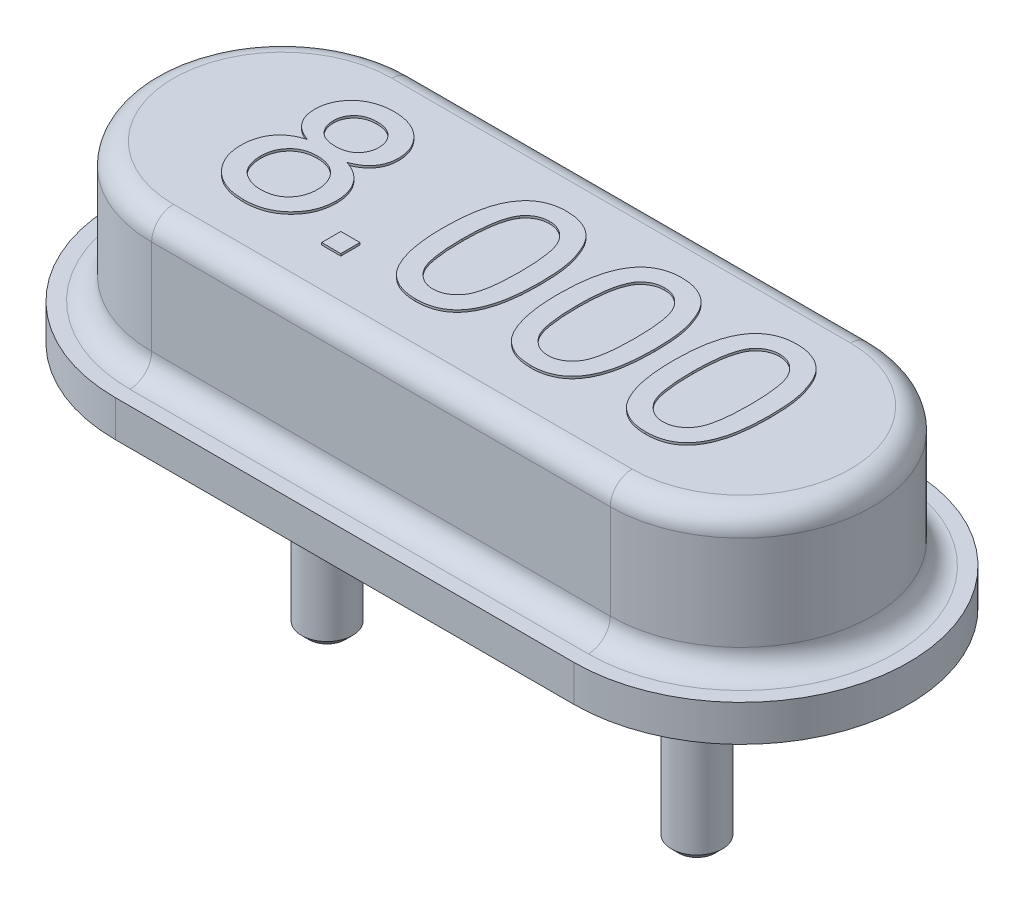
SolidWorks part; units mm, degrees
ref_plane "Front" through (0, 0, 0) normal (0, 0, 1) x (1, 0, 0)
ref_plane "Top" through (0, 0, 0) normal (0, 1, 0) x (1, 0, 0)
ref_plane "Right" through (0, 0, 0) normal (1, 0, 0) x (0, 0, -1)
sketch "Sketch1" plane through (0, 0, 0) normal (0, 1, 0) x (1, 0, 0)
  line L0 (-3.15, 0) -> (3.15, 0) construction
  line L1 (-3.15, 2.3) -> (3.15, 2.3)
  line L2 (-3.15, -2.3) -> (3.15, -2.3)
  arc A0 (-3.15, 2.3) -> (-3.15, -2.3) centre (-3.15, 0) ccw
  arc A1 (3.15, -2.3) -> (3.15, 2.3) centre (3.15, 0) ccw
  point P3 (0, 0)
  dimension "D2" = 10.9
  dimension "D1" = 4.6
extrude "Boss-Extrude1" add sketch "Sketch1" along normal blind 0.5
sketch "Sketch2" plane through (0, 0.5, 0) normal (0, 1, 0) x (1, 0, 0)
  line L4 (-3.15, -1.8) -> (3.15, -1.8)
  line L5 (3.15, 1.8) -> (-3.15, 1.8)
  line L6 (-3.15, -1.8) -> (3.15, -1.8)
  line L7 (3.15, 1.8) -> (-3.15, 1.8)
  arc A4 (-3.15, 1.8) -> (-3.15, -1.8) centre (-3.15, 0) ccw
  arc A5 (3.15, -1.8) -> (3.15, 1.8) centre (3.15, 0) ccw
  arc A6 (-3.15, 1.8) -> (-3.15, -1.8) centre (-3.15, 0) ccw
  arc A7 (3.15, -1.8) -> (3.15, 1.8) centre (3.15, 0) ccw
  dimension "D1" = 0.5
extrude "Boss-Extrude2" add sketch "Sketch2" along normal blind 1.9
fillet "Fillet1" radius 0.3 8 edges at (-4.95, 0.5, 0) (0, 0.5, -1.8) (4.95, 0.5, 0) (-4.95, 2.4, 0) (0, 2.4, -1.8) (4.95, 2.4, 0) (0, 0.5, 1.8) (0, 2.4, 1.8)
sketch "Sketch3" plane through (0, 2.4, 0) normal (0, 1, 0) x (1, 0, 0)
  line L0 (-3.4919, -0.9673) -> (3.4675, -0.9673) construction
  text T0 "8.000" font "Arial" height in points 8
extrude "Boss-Extrude3" add sketch "Sketch3" along normal blind 0.03
sketch "Sketch4" plane through (0, 0, 0) normal (0, -1, 0) x (1, 0, 0)
  line L0 (-2.54, 0) -> (2.54, 0) construction
  circle A0 centre (-2.54, 0) radius 0.35
  circle A1 centre (2.54, 0) radius 0.35
  dimension "D1" = 0.7
  dimension "D2" = 5.08
extrude "Boss-Extrude4" add sketch "Sketch4" along normal blind 3.1
chamfer "Chamfer1" distance 0.1 angle 45 2 edges at (2.54, -3.1, -0.35) (-2.54, -3.1, -0.35)
